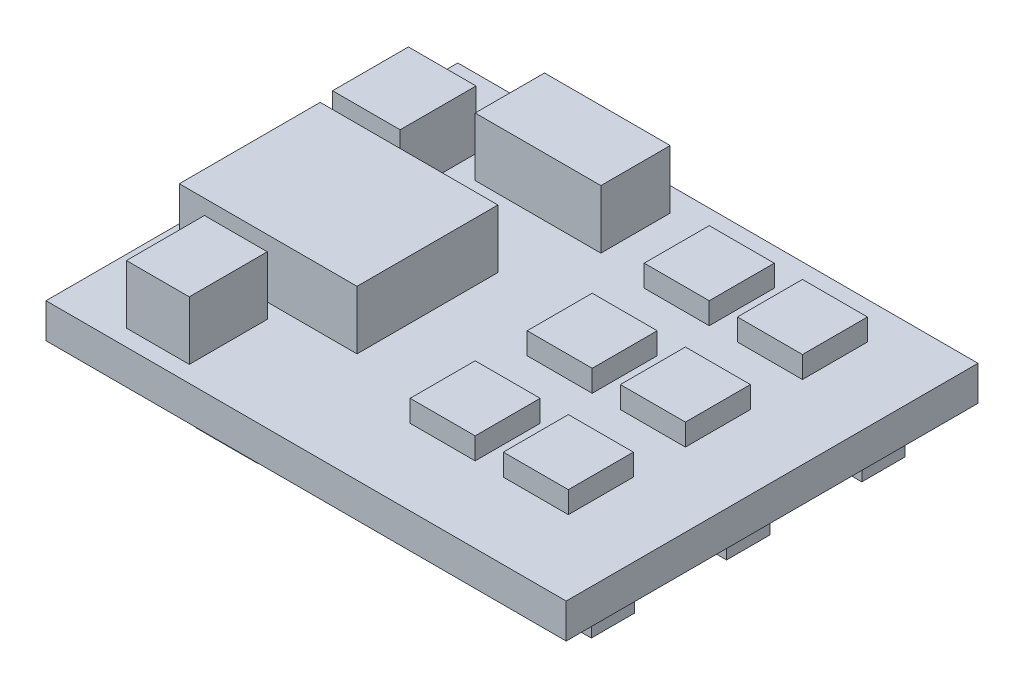
SolidWorks part; units mm, degrees
ref_plane "Front Plane" through (0, 0, 0) normal (0, 0, 1) x (1, 0, 0)
ref_plane "Top Plane" through (0, 0, 0) normal (0, 1, 0) x (1, 0, 0)
ref_plane "Right Plane" through (0, 0, 0) normal (1, 0, 0) x (0, 0, -1)
sketch "Sketch1" plane through (0, 0, 0) normal (0, 1, 0) x (1, 0, 0)
  line L1 (-8.5574, 8.4489) -> (15.4426, 8.4489)
  line L2 (-8.5574, 8.4489) -> (-8.5574, -10.5511)
  line L3 (-8.5574, -10.5511) -> (15.4426, -10.5511)
  line L4 (15.4426, 8.4489) -> (15.4426, -10.5511)
  dimension "D1" = 19
  dimension "D2" = 24
extrude "Boss-Extrude1" add sketch "Sketch1" along normal blind 1.6
sketch "Sketch2" plane through (0, 1.6, 0) normal (0, 1, 0) x (1, 0, 0)
  line L0 (-8.5574, 8.4489) -> (-8.5574, -10.5511) construction
  line L1 (-7.4574, 0.9989) -> (0.7426, 0.9989)
  line L2 (-7.4574, 0.9989) -> (-7.4574, -5.5011)
  line L3 (-7.4574, -5.5011) -> (0.7426, -5.5011)
  line L4 (0.7426, 0.9989) -> (0.7426, -5.5011)
  line L5 (-8.5574, -10.5511) -> (15.4426, -10.5511) construction
  line L6 (15.4426, 8.4489) -> (-8.5574, 8.4489) construction
  line L7 (-5.6074, -6.1911) -> (-2.7074, -6.1911)
  line L8 (-5.6074, -6.1911) -> (-5.6074, -9.7911)
  line L9 (-5.6074, -9.7911) -> (-2.7074, -9.7911)
  line L10 (-2.7074, -6.1911) -> (-2.7074, -9.7911)
  line L11 (-3.4574, 7.3489) -> (2.3426, 7.3489)
  line L12 (-3.4574, 7.3489) -> (-3.4574, 4.1489)
  line L13 (-3.4574, 4.1489) -> (2.3426, 4.1489)
  line L14 (2.3426, 7.3489) -> (2.3426, 4.1489)
  line L16 (-7.6374, 5.2489) -> (-4.5174, 5.2489)
  line L17 (-7.6374, 5.2489) -> (-7.6374, 1.7489)
  line L18 (-7.6374, 1.7489) -> (-4.5174, 1.7489)
  line L19 (-4.5174, 5.2489) -> (-4.5174, 1.7489)
  dimension "D1" = 6.5
  dimension "D2" = 8.2
  dimension "D3" = 9.3
  dimension "D4" = 11.55
  dimension "D5" = 3.6
  dimension "D6" = 2.9
  dimension "D7" = 5.85
  dimension "D8" = 10.79
  dimension "D9" = 5.8
  dimension "D10" = 3.2
  dimension "D11" = 10.9
  dimension "D12" = 4.3
  dimension "D13" = 3.12
  dimension "D14" = 3.5
  dimension "D15" = 6.7
  dimension "D16" = 4.04
extrude "Boss-Extrude2" add sketch "Sketch2" along normal blind 2.7 separate body
sketch "Sketch3" plane through (0, 1.6, 0) normal (0, 1, 0) x (1, 0, 0)
  line L0 (15.4426, -10.5511) -> (15.4426, 8.4489) construction
  line L1 (4.7426, 6.7489) -> (7.7426, 6.7489)
  line L2 (4.7426, 6.7489) -> (4.7426, 3.7489)
  line L3 (4.7426, 3.7489) -> (7.7426, 3.7489)
  line L4 (7.7426, 6.7489) -> (7.7426, 3.7489)
  line L5 (9.0426, 6.7489) -> (12.0426, 6.7489)
  line L6 (9.0426, 6.7489) -> (9.0426, 3.7489)
  line L7 (9.0426, 3.7489) -> (12.0426, 3.7489)
  line L8 (12.0426, 6.7489) -> (12.0426, 3.7489)
  line L9 (15.4426, 8.4489) -> (-8.5574, 8.4489) construction
  line L10 (4.7426, -1.6511) -> (7.7426, -1.6511)
  line L11 (4.7426, 1.3489) -> (4.7426, -1.6511)
  line L12 (4.7426, 1.3489) -> (7.7426, 1.3489)
  line L13 (7.7426, 1.3489) -> (7.7426, -1.6511)
  line L14 (9.0426, 1.3489) -> (12.0426, 1.3489)
  line L15 (9.0426, 1.3489) -> (9.0426, -1.6511)
  line L16 (9.0426, -1.6511) -> (12.0426, -1.6511)
  line L17 (12.0426, 1.3489) -> (12.0426, -1.6511)
  line L18 (4.7426, -7.0511) -> (7.7426, -7.0511)
  line L19 (4.7426, -4.0511) -> (4.7426, -7.0511)
  line L20 (4.7426, -4.0511) -> (7.7426, -4.0511)
  line L21 (7.7426, -4.0511) -> (7.7426, -7.0511)
  line L22 (9.0426, -4.0511) -> (12.0426, -4.0511)
  line L23 (9.0426, -4.0511) -> (9.0426, -7.0511)
  line L24 (9.0426, -7.0511) -> (12.0426, -7.0511)
  line L25 (12.0426, -4.0511) -> (12.0426, -7.0511)
  dimension "D1" = 3
  dimension "D2" = 3
  dimension "D3" = 3
  dimension "D4" = 7.3
  dimension "D5" = 3
  dimension "D6" = 10.7
  dimension "D7" = 4.7
  dimension "D8" = 3
extrude "Boss-Extrude3" add sketch "Sketch3" along normal blind 1 separate body contours L3 L4 L1 L2
sketch "Sketch4" plane through (0, 0, 0) normal (0, -1, 0) x (1, 0, 0)
  line L0 (-8.5574, 10.5511) -> (15.4426, 10.5511) construction
  line L1 (-3.9674, 8.2511) -> (-1.0674, 8.2511)
  line L2 (-3.9674, 8.2511) -> (-3.9674, 4.6511)
  line L3 (-3.9674, 4.6511) -> (-1.0674, 4.6511)
  line L4 (-1.0674, 8.2511) -> (-1.0674, 4.6511)
  line L5 (-7.0574, 4.7311) -> (-4.5574, 4.7311)
  line L6 (-7.0574, 4.7311) -> (-7.0574, 0.2311)
  line L7 (-7.0574, 0.2311) -> (-4.5574, 0.2311)
  line L8 (-4.5574, 4.7311) -> (-4.5574, 0.2311)
  line L9 (-7.9774, -0.9589) -> (-6.4774, -0.9589)
  line L10 (-7.9774, -0.9589) -> (-7.9774, -4.0989)
  line L11 (-7.9774, -4.0989) -> (-6.4774, -4.0989)
  line L12 (-6.4774, -0.9589) -> (-6.4774, -4.0989)
  line L13 (-8.5574, -8.4489) -> (-8.5574, 10.5511) construction
  line L14 (15.4426, -8.4489) -> (-8.5574, -8.4489) construction
  dimension "D1" = 2.9
  dimension "D2" = 3.6
  dimension "D3" = 5.9
  dimension "D4" = 4.5
  dimension "D5" = 2.5
  dimension "D6" = 10.32
  dimension "D7" = 7.49
  dimension "D8" = 4
  dimension "D9" = 3.14
  dimension "D10" = 1.5
  dimension "D11" = 7.49
  dimension "D12" = 2.08
extrude "Boss-Extrude4" add sketch "Sketch4" along normal blind 2.32 separate body
sketch "Sketch5" plane through (0, 0, 0) normal (0, -1, 0) x (1, 0, 0)
  line L0 (-8.5574, -8.4489) -> (-8.5574, 10.5511) construction
  line L1 (-1.7074, 3.8511) -> (6.2926, 3.8511)
  line L2 (-1.7074, 3.8511) -> (-1.7074, -4.1489)
  line L3 (-1.7074, -4.1489) -> (6.2926, -4.1489)
  line L4 (6.2926, 3.8511) -> (6.2926, -4.1489)
  line L5 (13.6426, 8.8511) -> (14.9026, 8.8511)
  line L6 (13.6426, 8.8511) -> (13.6426, 6.8511)
  line L7 (13.6426, 6.8511) -> (14.9026, 6.8511)
  line L8 (14.9026, 8.8511) -> (14.9026, 6.8511)
  line L9 (15.4426, -8.4489) -> (-8.5574, -8.4489) construction
  line L10 (15.4426, 10.5511) -> (15.4426, -8.4489) construction
  line L11 (-8.5574, 10.5511) -> (15.4426, 10.5511) construction
  line L12 (13.6426, 2.6111) -> (14.9026, 2.6111)
  line L13 (13.6426, 2.6111) -> (13.6426, 0.6111)
  line L14 (14.9026, 2.6111) -> (14.9026, 0.6111)
  line L15 (13.6426, 0.6111) -> (14.9026, 0.6111)
  line L16 (13.6426, -3.6289) -> (14.9026, -3.6289)
  line L17 (13.6426, -3.6289) -> (13.6426, -5.6289)
  line L18 (14.9026, -3.6289) -> (14.9026, -5.6289)
  line L19 (13.6426, -5.6289) -> (14.9026, -5.6289)
  dimension "D1" = 8
  dimension "D2" = 8
  dimension "D3" = 14.85
  dimension "D4" = 12.3
  dimension "D5" = 1.26
  dimension "D6" = 2
  dimension "D7" = 1.8
  dimension "D8" = 3.7
  dimension "D9" = 3
extrude "Boss-Extrude5" add sketch "Sketch5" along normal blind 1 separate body
